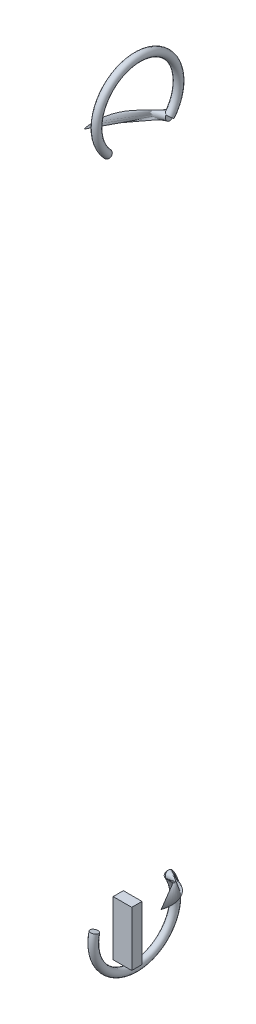
SolidWorks part; units mm, degrees
material "Plain Carbon Steel"
ref_plane "Front Plane" through (0, 0, 0) normal (0, 0, 1) x (1, 0, 0)
ref_plane "Top Plane" through (0, 0, 0) normal (0, 1, 0) x (1, 0, 0)
ref_plane "Right Plane" through (0, 0, 0) normal (1, 0, 0) x (0, 0, -1)
sketch "Sketch1" plane through (0, 0, 0) normal (0, 1, 0) x (1, 0, 0)
  circle A0 centre (0, 0) radius 2.3
  dimension "D1" = 4.6
curve "Helix/Spiral1" pitch 2 height 36 turns 18
sweep "Sweep1" add path "Helix/Spiral1" circular profile diameter 0.42 parameters "D3"=0.42
sketch "Sketch28" plane through (0, 0, 0) normal (1, 0, 0) x (0, 0, -1)
  arc A1 (2.3, 36) -> (-1.0812, 35.89) centre (0.5612, 37.4279) ccw
  spline S0 degree 3 poles (2.3, 0) (2.3, 0.0414) (2.1802, 0.1251) (1.6687, 0.25) (0.9031, 0.375) (0, 0.5) (-0.9031, 0.625) (-1.6687, 0.75) (-2.1802, 0.875) (-2.3599, 1) (-2.1802, 1.125) (-1.6687, 1.25) (-0.9031, 1.375) (0, 1.5) (0.9031, 1.625) (1.6687, 1.75) (2.1802, 1.875) (2.3599, 2) (2.1802, 2.125) (1.6687, 2.25) (0.9031, 2.375) (0, 2.5) (-0.9031, 2.625) (-1.6687, 2.75) (-2.1802, 2.875) (-2.3599, 3) (-2.1802, 3.125) (-1.6687, 3.25) (-0.9031, 3.375) (0, 3.5) (0.9031, 3.625) (1.6687, 3.75) (2.1802, 3.875) (2.3599, 4) (2.1802, 4.125) (1.6687, 4.25) (0.9031, 4.375) (0, 4.5) (-0.9031, 4.625) (-1.6687, 4.75) (-2.1802, 4.875) (-2.3599, 5) (-2.1802, 5.125) (-1.6687, 5.25) (-0.9031, 5.375) (0, 5.5) (0.9031, 5.625) (1.6687, 5.75) (2.1802, 5.875) (2.3599, 6) (2.1802, 6.125) (1.6687, 6.25) (0.9031, 6.375) (0, 6.5) (-0.9031, 6.625) (-1.6687, 6.75) (-2.1802, 6.875) (-2.3599, 7) (-2.1802, 7.125) (-1.6687, 7.25) (-0.9031, 7.375) (0, 7.5) (0.9031, 7.625) (1.6687, 7.75) (2.1802, 7.875) (2.3599, 8) (2.1802, 8.125) (1.6687, 8.25) (0.9031, 8.375) (0, 8.5) (-0.9031, 8.625) (-1.6687, 8.75) (-2.1802, 8.875) (-2.3599, 9) (-2.1802, 9.125) (-1.6687, 9.25) (-0.9031, 9.375) (0, 9.5) (0.9031, 9.625) (1.6687, 9.75) (2.1802, 9.875) (2.3599, 10) (2.1802, 10.125) (1.6687, 10.25) (0.9031, 10.375) (0, 10.5) (-0.9031, 10.625) (-1.6687, 10.75) (-2.1802, 10.875) (-2.3599, 11) (-2.1802, 11.125) (-1.6687, 11.25) (-0.9031, 11.375) (0, 11.5) (0.9031, 11.625) (1.6687, 11.75) (2.1802, 11.875) (2.3599, 12) (2.1802, 12.125) (1.6687, 12.25) (0.9031, 12.375) (0, 12.5) (-0.9031, 12.625) (-1.6687, 12.75) (-2.1802, 12.875) (-2.3599, 13) (-2.1802, 13.125) (-1.6687, 13.25) (-0.9031, 13.375) (0, 13.5) (0.9031, 13.625) (1.6687, 13.75) (2.1802, 13.875) (2.3599, 14) (2.1802, 14.125) (1.6687, 14.25) (0.9031, 14.375) (0, 14.5) (-0.9031, 14.625) (-1.6687, 14.75) (-2.1802, 14.875) (-2.3599, 15) (-2.1802, 15.125) (-1.6687, 15.25) (-0.9031, 15.375) (0, 15.5) (0.9031, 15.625) (1.6687, 15.75) (2.1802, 15.875) (2.3599, 16) (2.1802, 16.125) (1.6687, 16.25) (0.9031, 16.375) (0, 16.5) (-0.9031, 16.625) (-1.6687, 16.75) (-2.1802, 16.875) (-2.3599, 17) (-2.1802, 17.125) (-1.6687, 17.25) (-0.9031, 17.375) (0, 17.5) (0.9031, 17.625) (1.6687, 17.75) (2.1802, 17.875) (2.3599, 18) (2.1802, 18.125) (1.6687, 18.25) (0.9031, 18.375) (0, 18.5) (-0.9031, 18.625) (-1.6687, 18.75) (-2.1802, 18.875) (-2.3599, 19) (-2.1802, 19.125) (-1.6687, 19.25) (-0.9031, 19.375) (0, 19.5) (0.9031, 19.625) (1.6687, 19.75) (2.1802, 19.875) (2.3599, 20) (2.1802, 20.125) (1.6687, 20.25) (0.9031, 20.375) (0, 20.5) (-0.9031, 20.625) (-1.6687, 20.75) (-2.1802, 20.875) (-2.3599, 21) (-2.1802, 21.125) (-1.6687, 21.25) (-0.9031, 21.375) (0, 21.5) (0.9031, 21.625) (1.6687, 21.75) (2.1802, 21.875) (2.3599, 22) (2.1802, 22.125) (1.6687, 22.25) (0.9031, 22.375) (0, 22.5) (-0.9031, 22.625) (-1.6687, 22.75) (-2.1802, 22.875) (-2.3599, 23) (-2.1802, 23.125) (-1.6687, 23.25) (-0.9031, 23.375) (0, 23.5) (0.9031, 23.625) (1.6687, 23.75) (2.1802, 23.875) (2.3599, 24) (2.1802, 24.125) (1.6687, 24.25) (0.9031, 24.375) (0, 24.5) (-0.9031, 24.625) (-1.6687, 24.75) (-2.1802, 24.875) (-2.3599, 25) (-2.1802, 25.125) (-1.6687, 25.25) (-0.9031, 25.375) (0, 25.5) (0.9031, 25.625) (1.6687, 25.75) (2.1802, 25.875) (2.3599, 26) (2.1802, 26.125) (1.6687, 26.25) (0.9031, 26.375) (0, 26.5) (-0.9031, 26.625) (-1.6687, 26.75) (-2.1802, 26.875) (-2.3599, 27) (-2.1802, 27.125) (-1.6687, 27.25) (-0.9031, 27.375) (0, 27.5) (0.9031, 27.625) (1.6687, 27.75) (2.1802, 27.875) (2.3599, 28) (2.1802, 28.125) (1.6687, 28.25) (0.9031, 28.375) (0, 28.5) (-0.9031, 28.625) (-1.6687, 28.75) (-2.1802, 28.875) (-2.3599, 29) (-2.1802, 29.125) (-1.6687, 29.25) (-0.9031, 29.375) (0, 29.5) (0.9031, 29.625) (1.6687, 29.75) (2.1802, 29.875) (2.3599, 30) (2.1802, 30.125) (1.6687, 30.25) (0.9031, 30.375) (0, 30.5) (-0.9031, 30.625) (-1.6687, 30.75) (-2.1802, 30.875) (-2.3599, 31) (-2.1802, 31.125) (-1.6687, 31.25) (-0.9031, 31.375) (0, 31.5) (0.9031, 31.625) (1.6687, 31.75) (2.1802, 31.875) (2.3599, 32) (2.1802, 32.125) (1.6687, 32.25) (0.9031, 32.375) (0, 32.5) (-0.9031, 32.625) (-1.6687, 32.75) (-2.1802, 32.875) (-2.3599, 33) (-2.1802, 33.125) (-1.6687, 33.25) (-0.9031, 33.375) (0, 33.5) (0.9031, 33.625) (1.6687, 33.75) (2.1802, 33.875) (2.3599, 34) (2.1802, 34.125) (1.6687, 34.25) (0.9031, 34.375) (0, 34.5) (-0.9031, 34.625) (-1.6687, 34.75) (-2.1802, 34.875) (-2.3599, 35) (-2.1802, 35.125) (-1.6687, 35.25) (-0.9031, 35.375) (0, 35.5) (0.9031, 35.625) (1.6687, 35.75) (2.1802, 35.8749) (2.3, 35.9586) (2.3, 36) knots 0 0 0 0 0.003472 0.006944 0.010417 0.013889 0.017361 0.020833 0.024306 0.027778 0.03125 0.034722 0.038194 0.041667 0.045139 0.048611 0.052083 0.055556 0.059028 0.0625 0.065972 0.069444 0.072917 0.076389 0.079861 0.083333 0.086806 0.090278 0.09375 0.097222 0.100694 0.104167 0.107639 0.111111 0.114583 0.118056 0.121528 0.125 0.128472 0.131944 0.135417 0.138889 0.142361 0.145833 0.149306 0.152778 0.15625 0.159722 0.163194 0.166667 0.170139 0.173611 0.177083 0.180556 0.184028 0.1875 0.190972 0.194444 0.197917 0.201389 0.204861 0.208333 0.211806 0.215278 0.21875 0.222222 0.225694 0.229167 0.232639 0.236111 0.239583 0.243056 0.246528 0.25 0.253472 0.256944 0.260417 0.263889 0.267361 0.270833 0.274306 0.277778 0.28125 0.284722 0.288194 0.291667 0.295139 0.298611 0.302083 0.305556 0.309028 0.3125 0.315972 0.319444 0.322917 0.326389 0.329861 0.333333 0.336806 0.340278 0.34375 0.347222 0.350694 0.354167 0.357639 0.361111 0.364583 0.368056 0.371528 0.375 0.378472 0.381944 0.385417 0.388889 0.392361 0.395833 0.399306 0.402778 0.40625 0.409722 0.413194 0.416667 0.420139 0.423611 0.427083 0.430556 0.434028 0.4375 0.440972 0.444444 0.447917 0.451389 0.454861 0.458333 0.461806 0.465278 0.46875 0.472222 0.475694 0.479167 0.482639 0.486111 0.489583 0.493056 0.496528 0.5 0.503472 0.506944 0.510417 0.513889 0.517361 0.520833 0.524306 0.527778 0.53125 0.534722 0.538194 0.541667 0.545139 0.548611 0.552083 0.555556 0.559028 0.5625 0.565972 0.569444 0.572917 0.576389 0.579861 0.583333 0.586806 0.590278 0.59375 0.597222 0.600694 0.604167 0.607639 0.611111 0.614583 0.618056 0.621528 0.625 0.628472 0.631944 0.635417 0.638889 0.642361 0.645833 0.649306 0.652778 0.65625 0.659722 0.663194 0.666667 0.670139 0.673611 0.677083 0.680556 0.684028 0.6875 0.690972 0.694444 0.697917 0.701389 0.704861 0.708333 0.711806 0.715278 0.71875 0.722222 0.725694 0.729167 0.732639 0.736111 0.739583 0.743056 0.746528 0.75 0.753472 0.756944 0.760417 0.763889 0.767361 0.770833 0.774306 0.777778 0.78125 0.784722 0.788194 0.791667 0.795139 0.798611 0.802083 0.805556 0.809028 0.8125 0.815972 0.819444 0.822917 0.826389 0.829861 0.833333 0.836806 0.840278 0.84375 0.847222 0.850694 0.854167 0.857639 0.861111 0.864583 0.868056 0.871528 0.875 0.878472 0.881944 0.885417 0.888889 0.892361 0.895833 0.899306 0.902778 0.90625 0.909722 0.913194 0.916667 0.920139 0.923611 0.927083 0.930556 0.934028 0.9375 0.940972 0.944444 0.947917 0.951389 0.954861 0.958333 0.961806 0.965278 0.96875 0.972222 0.975694 0.979167 0.982639 0.986111 0.989583 0.993056 0.996528 1 1 1 1 construction
  dimension "D1" = 2.25
sweep "Sweep2" add path "Sketch28" circular profile diameter 0.42 parameters "D3"=0.42
sketch "Sketch43" plane through (0, 0, 0) normal (1, 0, 0) x (0, 0, -1)
  arc A0 (2.3, 0) -> (-1.8007, -0.6645) centre (0.388, -1.1861) cw
  dimension "D1" = 2.25
sweep "Sweep3" add path "Sketch43" circular profile diameter 0.42 parameters "D3"=0.42
sketch "Sketch44" plane through (0, 0, 0) normal (0, 1, 0) x (1, 0, 0)
  line L1 (-0.4889, 0.2753) -> (0.532, 0.2753)
  line L2 (-0.4889, 0.2753) -> (-0.4889, -0.2855)
  line L3 (-0.4889, -0.2855) -> (0.532, -0.2855)
  line L4 (0.532, 0.2753) -> (0.532, -0.2855)
extrude "Boss-Extrude1" add sketch "Sketch44" against normal blind 3 separate body
